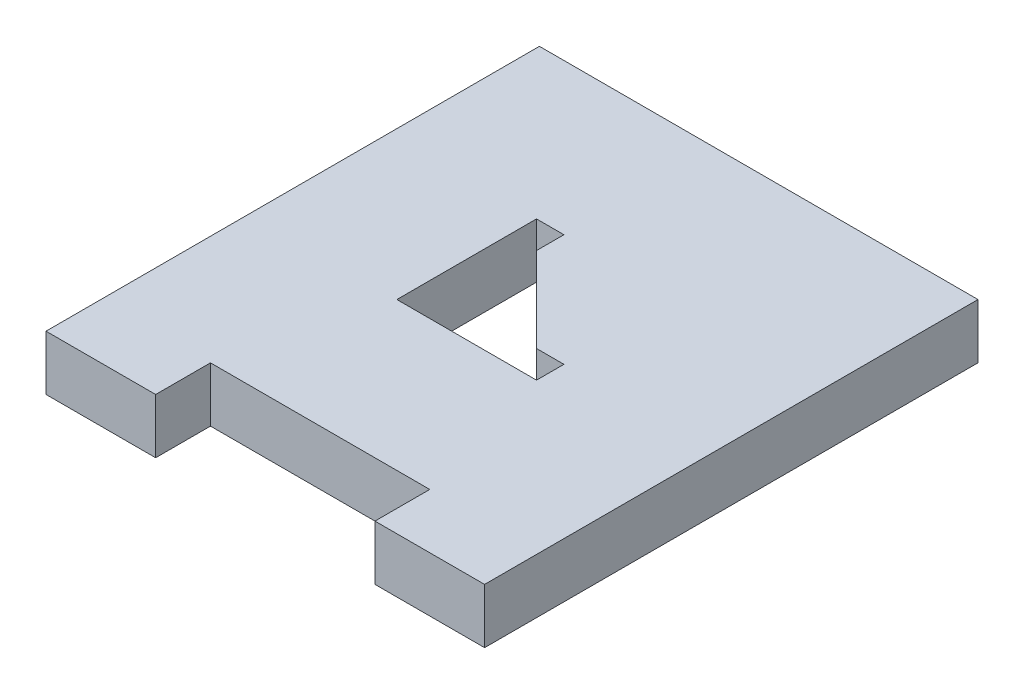
SolidWorks part; units mm, degrees
ref_plane "Front Plane" through (0, 0, 0) normal (0, 0, 1) x (1, 0, 0)
ref_plane "Top Plane" through (0, 0, 0) normal (0, 1, 0) x (1, 0, 0)
ref_plane "Right Plane" through (0, 0, 0) normal (1, 0, 0) x (0, 0, -1)
sketch "Sketch1" plane through (0, 0, 0) normal (0, 1, 0) x (1, 0, 0)
  line L0 (-4.1275, -4.1275) -> (-4.1275, 3.9599)
  line L1 (-12.7, -12.7) -> (12.7, -12.7)
  line L2 (-12.7, -12.7) -> (-12.7, 12.7)
  line L3 (-12.7, 12.7) -> (12.7, 12.7)
  line L4 (12.7, -12.7) -> (12.7, 12.7)
  line L5 (-12.7, -12.7) -> (12.7, 12.7) construction
  line L6 (-12.7, 12.7) -> (12.7, -12.7) construction
  line L7 (-4.1275, 3.9599) -> (-2.54, 3.9599)
  line L8 (-2.54, 3.9599) -> (-2.54, -2.54)
  line L9 (3.9599, -4.1275) -> (3.9599, -2.54)
  line L10 (3.9599, -2.54) -> (-2.54, -2.54)
  line L11 (-4.1275, -4.1275) -> (3.9599, -4.1275)
  point P0 (0, 0)
  dimension "D1" = 25.4
  dimension "D2" = 25.4
  dimension "D3" = 1.5875
  dimension "D4" = 2.54
  dimension "D5" = 8.0874
extrude "Boss-Extrude1" add sketch "Sketch1" along normal blind 3.175
sketch "Sketch2" plane through (0, 0, 12.7) normal (0, 0, 1) x (1, 0, 0)
  line L0 (-12.7, 0) -> (12.7, 0) construction
  line L1 (-12.7, 3.175) -> (-6.35, 3.175)
  line L2 (-12.7, 3.175) -> (-12.7, 0)
  line L3 (-12.7, 0) -> (-6.35, 0)
  line L4 (-6.35, 3.175) -> (-6.35, 0)
  line L6 (12.7, 3.175) -> (6.35, 3.175)
  line L7 (12.7, 3.175) -> (12.7, 0)
  line L8 (12.7, 0) -> (6.35, 0)
  line L9 (6.35, 3.175) -> (6.35, 0)
  dimension "D1" = 6.35
  dimension "D2" = 6.35
extrude "Boss-Extrude2" add sketch "Sketch2" along normal blind 3.175
sketch "Sketch3" plane through (0, 3.175, 0) normal (0, 1, 0) x (1, 0, 0)
  line L0 (-4.1275, 3.9599) -> (3.9599, -4.1275) construction
  line L1 (-2.54, 2.3724) -> (-2.54, -2.54)
  line L2 (-2.54, -2.54) -> (-2.54, 3.9599) construction
  line L3 (-2.54, -2.54) -> (2.3724, -2.54)
  line L4 (3.9599, -2.54) -> (-2.54, -2.54) construction
  line L5 (2.3724, -2.54) -> (-2.54, 2.3724)
extrude "Cut-Extrude1" cut sketch "Sketch3" against normal blind 6.35
